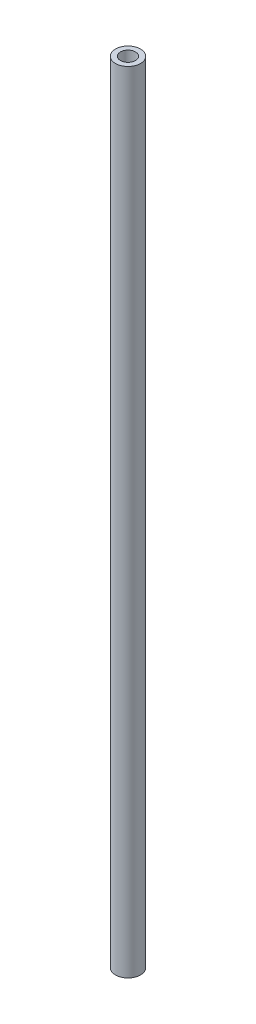
SolidWorks part; units mm, degrees
material "3003-O"
ref_plane "Front Plane" through (0, 0, 0) normal (0, 0, 1) x (1, 0, 0)
ref_plane "Top Plane" through (0, 0, 0) normal (0, 1, 0) x (1, 0, 0)
ref_plane "Right Plane" through (0, 0, 0) normal (1, 0, 0) x (0, 0, -1)
sketch "Sketch1" plane through (0, 0, 0) normal (0, 1, 0) x (1, 0, 0)
  circle A0 centre (0, 0) radius 1.5875
  circle A1 centre (0, 0) radius 0.9525
  dimension "D1" = 3.175
  dimension "D2" = 1.905
extrude "Boss-Extrude1" add sketch "Sketch1" along normal mid plane 100
